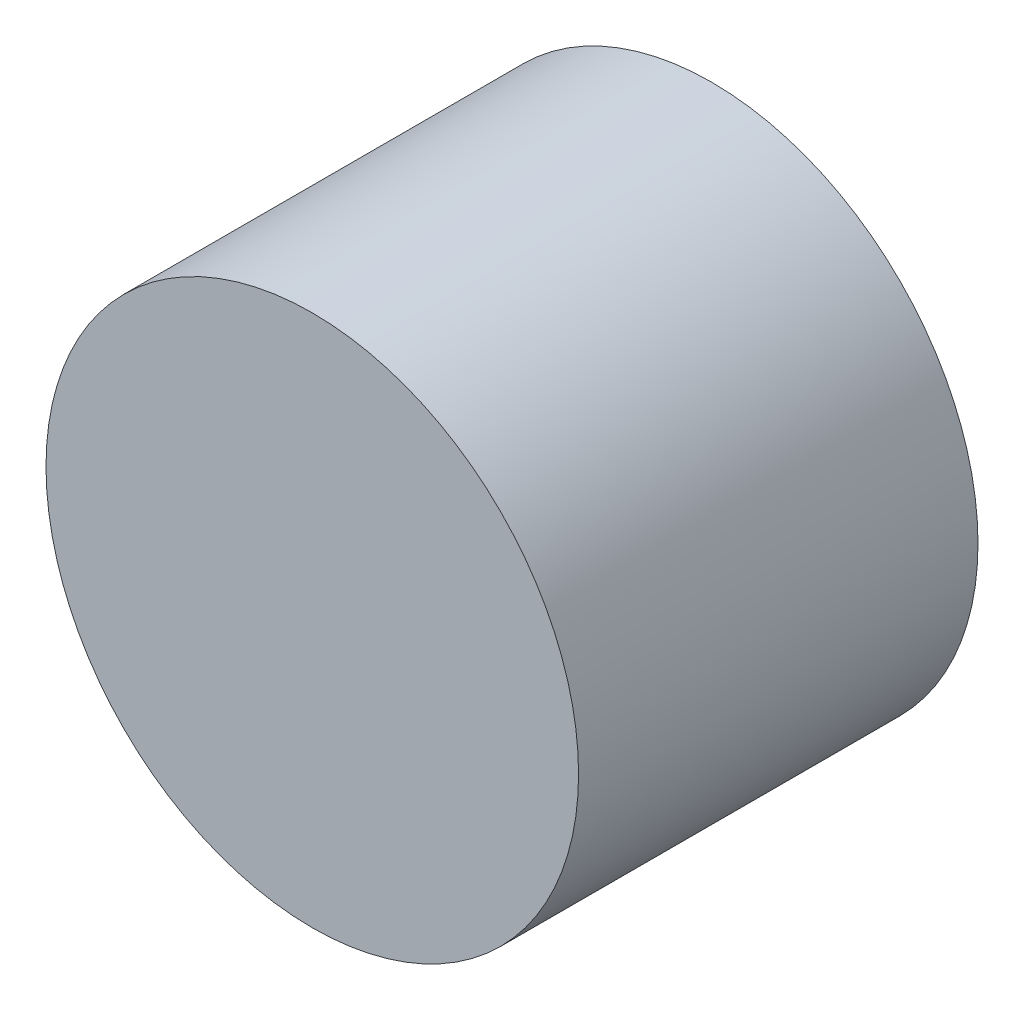
SolidWorks part; units mm, degrees
ref_plane "Plan de face" through (0, 0, 0) normal (0, 0, 1) x (1, 0, 0)
ref_plane "Plan de dessus" through (0, 0, 0) normal (0, 1, 0) x (1, 0, 0)
ref_plane "Plan de droite" through (0, 0, 0) normal (1, 0, 0) x (0, 0, -1)
sketch "Esquisse1" plane through (0, 0, 0) normal (0, 0, 1) x (1, 0, 0)
  circle A0 centre (0, 0) radius 4
  dimension "D1" = 8
extrude "Boss.-Extru.1" add sketch "Esquisse1" along normal blind 6
